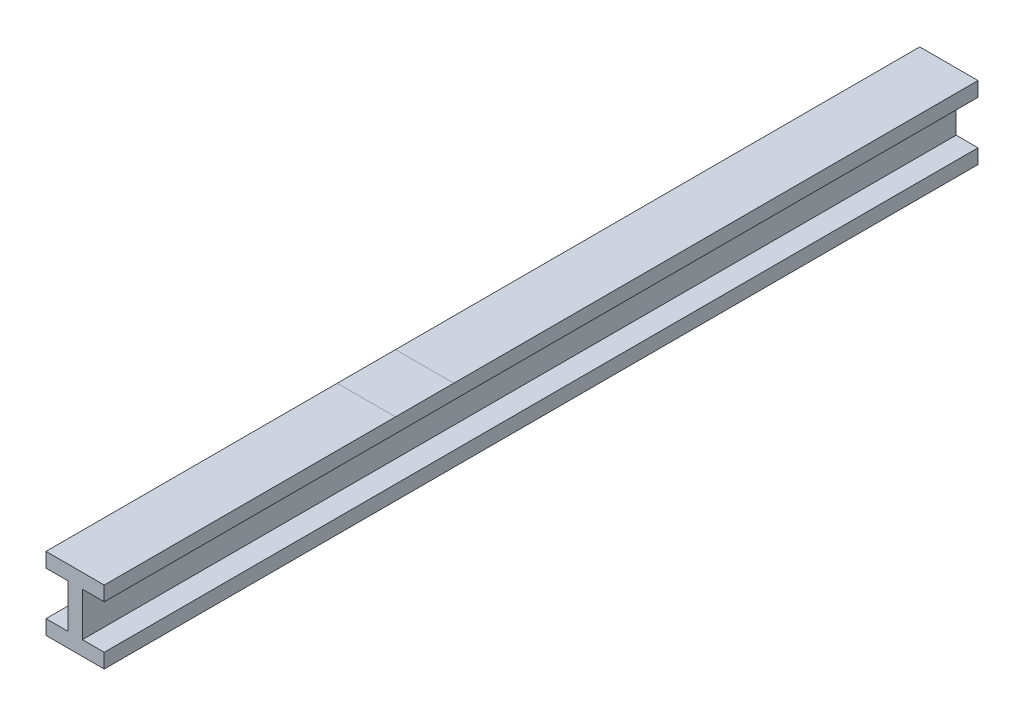
SolidWorks part; units mm, degrees
ref_plane "Płaszczyzna przednia" through (0, 0, 0) normal (0, 0, 1) x (1, 0, 0)
ref_plane "Płaszczyzna górna" through (0, 0, 0) normal (0, 1, 0) x (1, 0, 0)
ref_plane "Płaszczyzna prawa" through (0, 0, 0) normal (1, 0, 0) x (0, 0, -1)
sketch "Szkic1" plane through (0, 0, 0) normal (0, 0, 1) x (1, 0, 0)
  line L0 (0, 0) -> (200, 0)
  line L1 (200, 0) -> (200, 50)
  line L2 (200, 50) -> (125, 50)
  line L3 (125, 50) -> (125, 200)
  line L4 (125, 200) -> (200, 200)
  line L5 (200, 200) -> (200, 250)
  line L6 (200, 250) -> (0, 250)
  line L7 (0, 250) -> (0, 200)
  line L8 (0, 200) -> (75, 200)
  line L9 (75, 200) -> (75, 50)
  line L10 (75, 50) -> (0, 50)
  line L11 (0, 50) -> (0, 0)
  dimension "D1" = 200
  dimension "D2" = 250
  dimension "D3" = 150
  dimension "D4" = 75
  dimension "D6" = 50
extrude "Dodanie-wyciągnięcie1" add sketch "Szkic1" against normal blind 3000
sketch "Szkic2" plane through (0, 250, 0) normal (0, 1, 0) x (1, 0, 0)
  line L0 (200, 3000) -> (200, 0) construction
  line L1 (0, 1000) -> (200, 1000)
  line L2 (0, 1000) -> (0, 1200)
  line L3 (0, 1200) -> (200, 1200)
  line L4 (200, 1000) -> (200, 1200)
  line L5 (0, 1000) -> (200, 1200) construction
  line L6 (0, 1200) -> (200, 1000) construction
  line L7 (200, 3000) -> (0, 3000) construction
  point P0 (100, 1100)
  point P9 (0, 0)
  point P10 (0, 0)
  dimension "D1" = 200
  dimension "D2" = 1900
split line "Linia podziałowa6"
